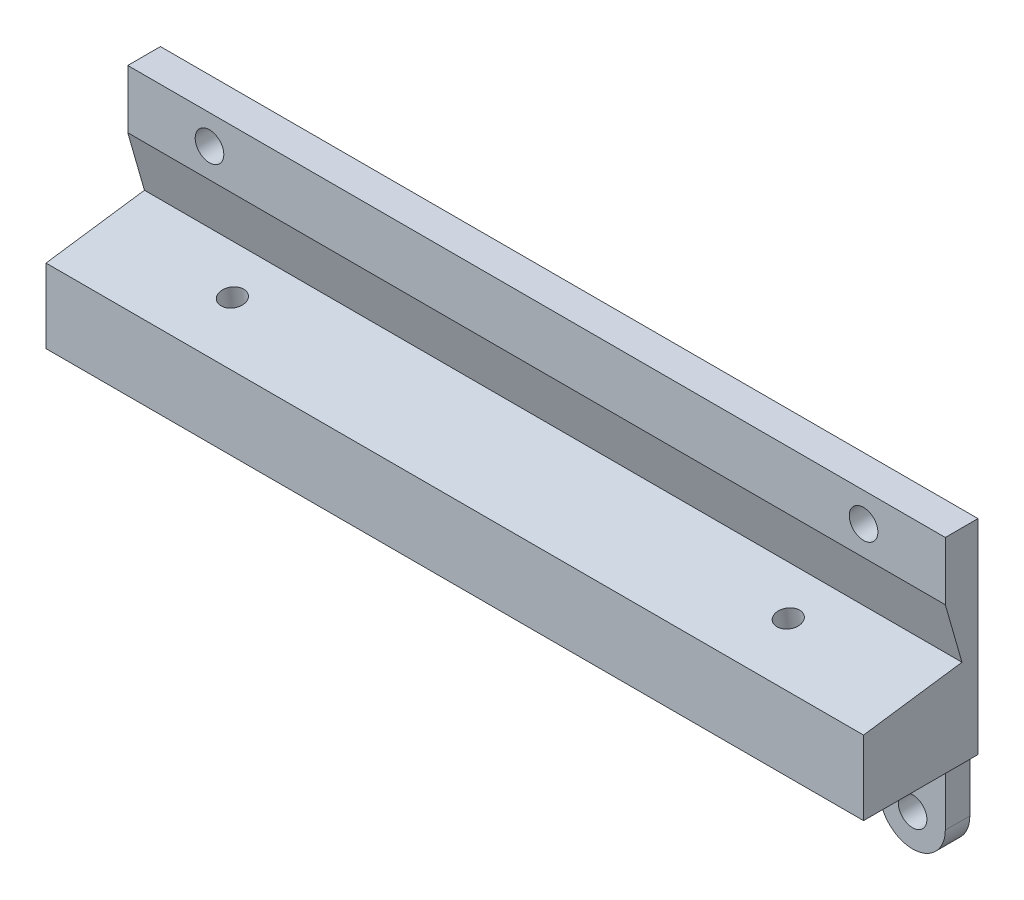
SolidWorks part; units mm, degrees
ref_plane "정면" through (0, 0, 0) normal (0, 0, 1) x (1, 0, 0)
ref_plane "윗면" through (0, 0, 0) normal (0, 1, 0) x (1, 0, 0)
ref_plane "우측면" through (0, 0, 0) normal (1, 0, 0) x (0, 0, -1)
sketch "스케치1" plane through (0, 0, 0) normal (0, 0, 1) x (1, 0, 0)
  line L1 (0, 0) -> (100, 0)
  line L2 (0, 0) -> (0, 25)
  line L3 (0, 25) -> (100, 25)
  line L4 (100, 0) -> (100, 25)
  dimension "D1" = 25
  dimension "D2" = 100
extrude "보스-돌출1" add sketch "스케치1" along normal blind 4
sketch "스케치2" plane through (0, 0, 4) normal (0, 0, 1) x (1, 0, 0)
  line L1 (100, 0) -> (0, 0)
  line L2 (100, 0) -> (100, 10.76)
  line L3 (100, 10.76) -> (0, 10.76)
  line L4 (0, 0) -> (0, 10.76)
  line L5 (100, 25) -> (0, 25) construction
  dimension "D1" = 14.24
extrude "보스-돌출2" add sketch "스케치2" along normal blind 10
sketch "스케치5" plane through (0, 0, 0) normal (-1, 0, 0) x (0, 0, 1)
  line L0 (1.96, 10.76) -> (19, 8.3652)
  line L1 (1.96, 10.76) -> (4, 17.8743)
  line L2 (4, 17.8743) -> (19, 8.3652)
  line L3 (0, 25) -> (0, 0) construction
  line L4 (4, 25) -> (4, 10.76) construction
  line L6 (14, 10.76) -> (4, 10.76) construction
  line L7 (14, 10.76) -> (14, 0) construction
  point P5 (0, 0)
  point P8 (0, 0)
  point P9 (22.1711, 8.9134)
  point P10 (0, 0)
  point P11 (0, 0)
  dimension "D1" = 82
  dimension "D2" = 82
  dimension "D3" = 1.96
  dimension "D4" = 5
extrude "컷-돌출1" cut sketch "스케치5" against normal through all
sketch "스케치6" plane through (0, 10.8217, 1.5209) normal (0, 0.9903, 0.1392) x (1, 0, 0)
  line L0 (16, -5.7417) -> (84, -5.7417) construction
  line L1 (0, -0.4434) -> (0, -12.6017) construction
  line L2 (0, -12.6017) -> (100, -12.6017) construction
  circle A0 centre (16, -5.7417) radius 1.4
  circle A1 centre (84, -5.7417) radius 1.4
  dimension "D2" = 16
  dimension "D4" = 2.8
  dimension "D1" = 68
  dimension "D3" = 6.86
extrude "컷-돌출2" cut sketch "스케치6" against normal through all
sketch "스케치7" plane through (0, 0, 0) normal (0, 0, -1) x (-1, 0, 0)
  line L0 (-95, -7) -> (-5, -7) construction
  line L1 (-100, 0) -> (-100, 25) construction
  line L2 (0, 0) -> (-100, 0) construction
  line L5 (-99, -7) -> (-99, 0)
  line L6 (-99, 0) -> (-91, 0)
  line L7 (-91, -7) -> (-91, 0)
  line L9 (-9, -7) -> (-9, 0)
  line L10 (-9, 0) -> (-1, 0)
  line L11 (-1, -7) -> (-1, 0)
  arc A0 (-99, -7) -> (-91, -7) centre (-95, -7) ccw
  arc A1 (-9, -7) -> (-1, -7) centre (-5, -7) ccw
  circle A2 centre (-95, -7) radius 1.75
  circle A3 centre (-5, -7) radius 1.75
  dimension "D2" = 5
  dimension "D3" = 8
  dimension "D5" = 3.5
  dimension "D1" = 90
  dimension "D4" = 7
extrude "보스-돌출3" add sketch "스케치7" against normal blind 3
sketch "스케치8" plane through (0, 0, 4) normal (0, 0, 1) x (1, 0, 0)
  line L0 (0, 21.4372) -> (100, 21.4372) construction
  line L1 (0, 25) -> (0, 17.8743) construction
  line L2 (100, 17.8743) -> (100, 25) construction
  circle A0 centre (10, 21.4372) radius 1.75
  circle A1 centre (90, 21.4372) radius 1.75
  dimension "D1" = 3.5
  dimension "D2" = 80
  dimension "D3" = 10
extrude "컷-돌출3" cut sketch "스케치8" against normal through all
